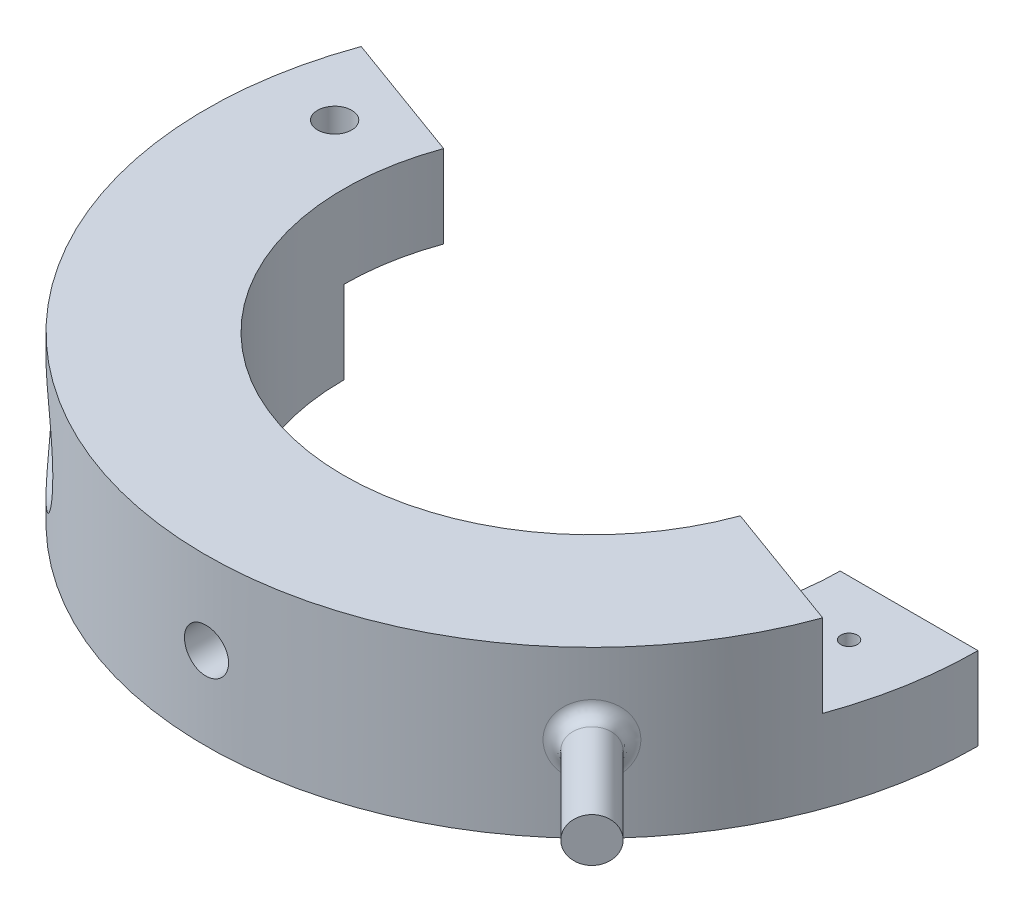
SolidWorks part; units mm, degrees
ref_plane "Front Plane" through (0, 0, 0) normal (0, 0, 1) x (1, 0, 0)
ref_plane "Top Plane" through (0, 0, 0) normal (0, 1, 0) x (1, 0, 0)
ref_plane "Right Plane" through (0, 0, 0) normal (1, 0, 0) x (0, 0, -1)
sketch "Sketch2" plane through (0, 0, 0) normal (0, 1, 0) x (1, 0, 0)
  line L0 (-70, 0) -> (-45, 0)
  line L1 (45, 0) -> (70, 0)
  arc A0 (45, 0) -> (-45, 0) centre (0, 0) cw
  arc A1 (-70, 0) -> (70, 0) centre (0, 0) ccw
  dimension "D1" = 45
  dimension "D2" = 25
  dimension "D3" = 70
extrude "Boss-Extrude1" add sketch "Sketch2" along normal blind 30
sketch "Sketch3" plane through (0, 30, 0) normal (0, 1, 0) x (1, 0, 0)
  line L0 (-45, 0) -> (-70, 0) construction
  line L1 (-65.7785, 23.9414) -> (-42.2862, 15.3909)
  line L2 (-70, 0) -> (-45, 0)
  arc A0 (-45, 0) -> (-42.2862, 15.3909) centre (0, 0) cw
  arc A1 (-70, 0) -> (-65.7785, 23.9414) centre (0, 0) cw
  arc A2 (-70, 0) -> (70, 0) centre (0, 0) ccw construction
extrude "Boss-Extrude2" add sketch "Sketch3" against normal blind 15
sketch "Sketch4" plane through (0, 30, 0) normal (0, 1, 0) x (1, 0, 0)
  line L0 (45, 0) -> (70, 0)
  line L1 (42.2862, -15.3909) -> (65.7785, -23.9414)
  arc A0 (70, 0) -> (65.7785, -23.9414) centre (0, 0) cw
  arc A1 (45, 0) -> (42.2862, -15.3909) centre (0, 0) cw
extrude "Cut-Extrude1" cut sketch "Sketch4" against normal blind 15
sketch "Sketch5" plane through (0, 15, 0) normal (0, 1, 0) x (1, 0, 0)
  line L0 (70, 0) -> (45, 0) construction
  line L1 (42.2862, -15.3909) -> (65.7785, -23.9414) construction
  circle A0 centre (56.6238, -10) radius 1.5
  arc A1 (42.2862, -15.3909) -> (45, 0) centre (0, 0) ccw construction
  arc A2 (65.7785, -23.9414) -> (70, 0) centre (0, 0) ccw construction
  dimension "D1" = 57.5
  dimension "D4" = 3
  dimension "D2" = 10
  dimension "D3" = 9.9695
  dimension "D5" = 57.5
extrude "Cut-Extrude2" cut sketch "Sketch5" against normal blind 15
sketch "Sketch6" plane through (0, 0, 0) normal (0, -1, 0) x (1, 0, 0)
  line L0 (56.6238, 11.5) -> (56.6238, 8.5)
  circle A2 centre (56.6238, 10) radius 1.5 construction
  circle A3 centre (56.6238, 10) radius 3.1
  circle A4 centre (56.6238, 10) radius 1.5
  point P8 (56.6238, 10)
extrude "Cut-Extrude4" cut sketch "Sketch6" against normal blind 5 contours A3
sketch "Sketch7" plane through (0, 15, 0) normal (0, -1, 0) x (1, 0, 0)
  line L0 (-42.2862, -15.3909) -> (-65.7785, -23.9414) construction
  line L1 (-45, 0) -> (-70, 0) construction
  circle A0 centre (-56.6291, -9.9695) radius 1.5
  dimension "D1" = 57.5
  dimension "D4" = 3
  dimension "D2" = 10
  dimension "D3" = 9.9695
extrude "Cut-Extrude5" cut sketch "Sketch7" against normal blind 15
sketch "Sketch8" plane through (0, 30, 0) normal (0, 1, 0) x (1, 0, 0)
  line L0 (-58.1291, 9.9695) -> (-55.1291, 9.9695) construction
  circle A0 centre (-56.6291, 9.9695) radius 1.5 construction
sketch "Sketch9" plane through (0, 30, 0) normal (0, 1, 0) x (1, 0, 0)
  line L0 (-56.6291, 11.4695) -> (-56.6291, 8.4695) construction
  circle A0 centre (-56.6291, 9.9695) radius 1.5 construction
sketch "Sketch10" plane through (0, 30, 0) normal (0, 1, 0) x (1, 0, 0)
  line L0 (-58.1291, 9.9695) -> (-55.1291, 9.9695) construction
  circle A0 centre (-56.6291, 9.9695) radius 3.1
  dimension "D1" = 6.2
extrude "Cut-Extrude6" cut sketch "Sketch10" against normal blind 5
ref_plane "Plane1" through (0, 0, 70) normal (0, 0, 1) x (1, 0, 0)
sketch "Sketch11" plane through (0, 0, 70) normal (0, 0, 1) x (1, 0, 0)
  line L0 (0, 30) -> (0, 0)
  line L2 (65.7785, 30) -> (-70, 30) construction
  circle A0 centre (0, 15) radius 4
  point P3 (0, 15)
  dimension "D1" = 30
  dimension "D2" = 8
extrude "Cut-Extrude8" cut sketch "Sketch11" against normal blind 30 contours A0
ref_plane "Plane2" through (49.4975, 0, 49.4975) normal (0.7071, 0, 0.7071) x (0, -1, 0)
sketch "Sketch13" plane through (49.4975, 0, 49.4975) normal (0.7071, 0, 0.7071) x (0, -1, 0)
  line L0 (0, 0) -> (-30, 0) construction
  line L1 (-30, 29.5833) -> (-30, -70) construction
  circle A0 centre (-15.3029, 0) radius 4
  dimension "D1" = 8
extrude "Boss-Extrude3" add sketch "Sketch13" along normal blind 22 and the other way blind 10
ref_plane "Plane3" through (-49.4975, 0, 49.4975) normal (-0.7071, 0, 0.7071) x (0, -1, 0)
sketch "Sketch14" plane through (-49.4975, 0, 49.4975) normal (-0.7071, 0, 0.7071) x (0, -1, 0)
  line L0 (0, 0) -> (-30, 0) construction
  line L1 (-30, 70) -> (-30, -63.4415) construction
sketch "Sketch15" plane through (-49.4975, 0, 49.4975) normal (-0.7071, 0, 0.7071) x (0, -1, 0)
  line L0 (0, 0) -> (-30, 0) construction
  circle A0 centre (-15, 0) radius 7.5
extrude "Cut-Extrude9" cut sketch "Sketch15" against normal blind 30 contours A0
sketch "Sketch16" plane through (-49.4975, 0, 49.4975) normal (-0.7071, 0, 0.7071) x (0, -1, 0)
  line L0 (0, 0) -> (-30, 0) construction
  circle A0 centre (-15, 0) radius 11
  dimension "D1" = 22
extrude "Cut-Extrude10" cut sketch "Sketch16" against normal blind 20 contours A0
fillet "Fillet2" radius 2.5 1 edges at (46.667, 16.2156, 52.1746)
